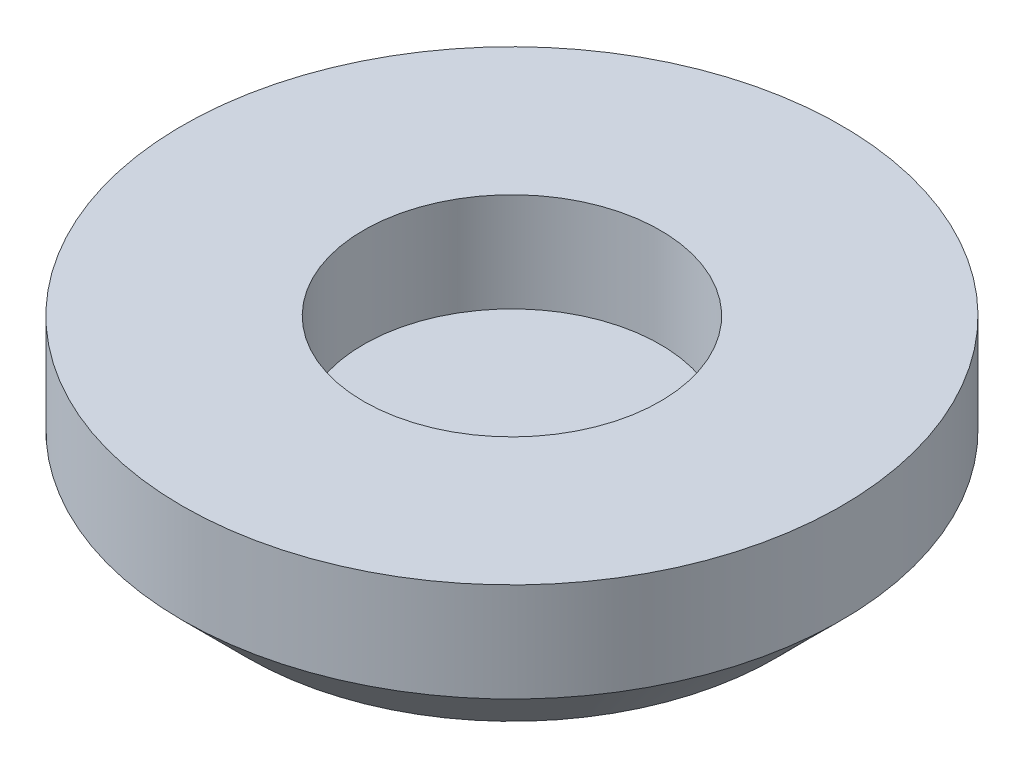
SolidWorks part; units mm, degrees
ref_plane "前基準面" through (0, 0, 0) normal (0, 0, 1) x (1, 0, 0)
ref_plane "上基準面" through (0, 0, 0) normal (0, 1, 0) x (1, 0, 0)
ref_plane "右基準面" through (0, 0, 0) normal (1, 0, 0) x (0, 0, -1)
sketch "草圖1" plane through (0, 0, 0) normal (0, 1, 0) x (1, 0, 0)
  circle A0 centre (0, 0) radius 10
  dimension "D1" = 20
extrude "填料-伸長1" add sketch "草圖1" along normal blind 5
sketch "草圖2" plane through (0, 5, 0) normal (0, 1, 0) x (1, 0, 0)
  circle A0 centre (0, 0) radius 4.5
  dimension "D1" = 9
extrude "除料-伸長1" cut sketch "草圖2" against normal blind 3
chamfer "導角1" distance 2 angle 45 1 edges at (0, 0, 10)
